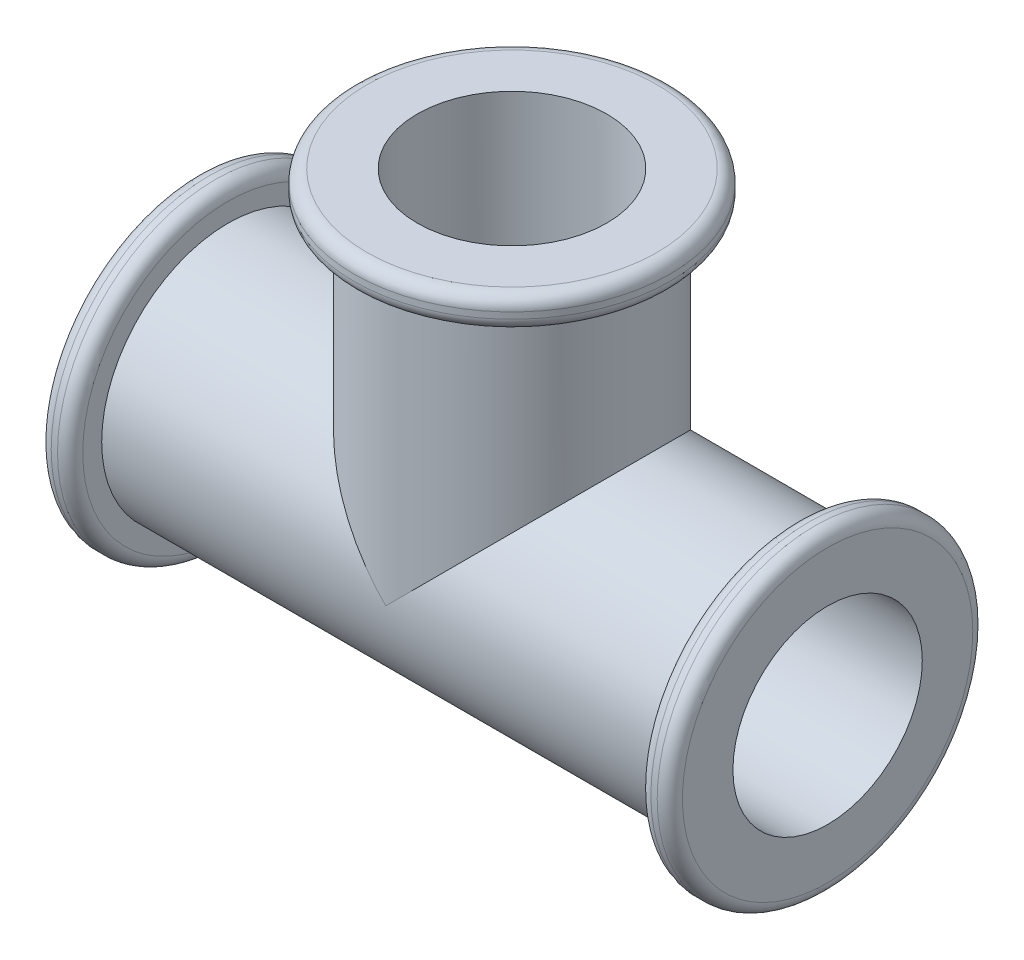
SolidWorks part; units mm, degrees
ref_plane "Front Plane" through (0, 0, 0) normal (0, 0, 1) x (1, 0, 0)
ref_plane "Top Plane" through (0, 0, 0) normal (0, 1, 0) x (1, 0, 0)
ref_plane "Right Plane" through (0, 0, 0) normal (1, 0, 0) x (0, 0, -1)
sketch "Sketch1" plane through (0, 0, 0) normal (1, 0, 0) x (0, 0, -1)
  circle A0 centre (0, 0) radius 10
  circle A1 centre (0, 0) radius 7.5
  dimension "D1" = 20
  dimension "D2" = 15
extrude "Boss-Extrude1" add sketch "Sketch1" along normal mid plane 50
sketch "Sketch2" plane through (25, 0, 0) normal (1, 0, 0) x (0, 0, -1)
  circle A0 centre (0, 0) radius 12.5
  circle A1 centre (0, 0) radius 7.5 construction
  circle A2 centre (0, 0) radius 7.5
  dimension "D1" = 25
extrude "Boss-Extrude2" add sketch "Sketch2" against normal blind 2.5 contours A0
mirror "Mirror1" about plane through (0, 0, 0) normal (1, 0, 0) of "Boss-Extrude2"
ref_plane "Plane1" through (0, 25, 0) normal (0, 1, 0) x (1, 0, 0)
sketch "Sketch3" plane through (0, 25, 0) normal (0, 1, 0) x (1, 0, 0)
  circle A0 centre (0, 0) radius 10
  circle A1 centre (0, 0) radius 7.5
  dimension "D1" = 20
  dimension "D2" = 15
extrude "Boss-Extrude3" add sketch "Sketch3" against normal up to next
sketch "Sketch5" plane through (0, 25, 0) normal (0, 1, 0) x (1, 0, 0)
  circle A0 centre (0, 0) radius 12.5
  circle A1 centre (0, 0) radius 7.5 construction
  circle A2 centre (0, 0) radius 7.5
  dimension "D1" = 25
extrude "Boss-Extrude4" add sketch "Sketch5" against normal blind 2.5
hole_wizard "Hole1" positions "Sketch6" profile "Sketch7" legacy end condition through all
sketch "Sketch6" plane through (25, 0, 0) normal (1, 0, 0) x (0, 0, -1)
  point P0 (0, 0)
sketch "Sketch7" plane through (25, 0, 0) normal (0, 1, 0) x (0, 0, -1)
  line L0 (0, 0) -> (0, 50)
  line L1 (0, 50) -> (7.5, 50)
  line L2 (7.5, 50) -> (7.5, 0)
  line L3 (7.5, 0) -> (0, 0)
  line L4 (0, 110) -> (0, -10) construction
  dimension "Diameter" = 15
  dimension "Depth" = 50
fillet "Fillet1" radius 1 6 edges at (0, 25, 12.5) (-25, 0, -12.5) (-22.5, 0, -12.5) (22.5, 0, -12.5) (25, 0, -12.5) (0, 22.5, 12.5)
